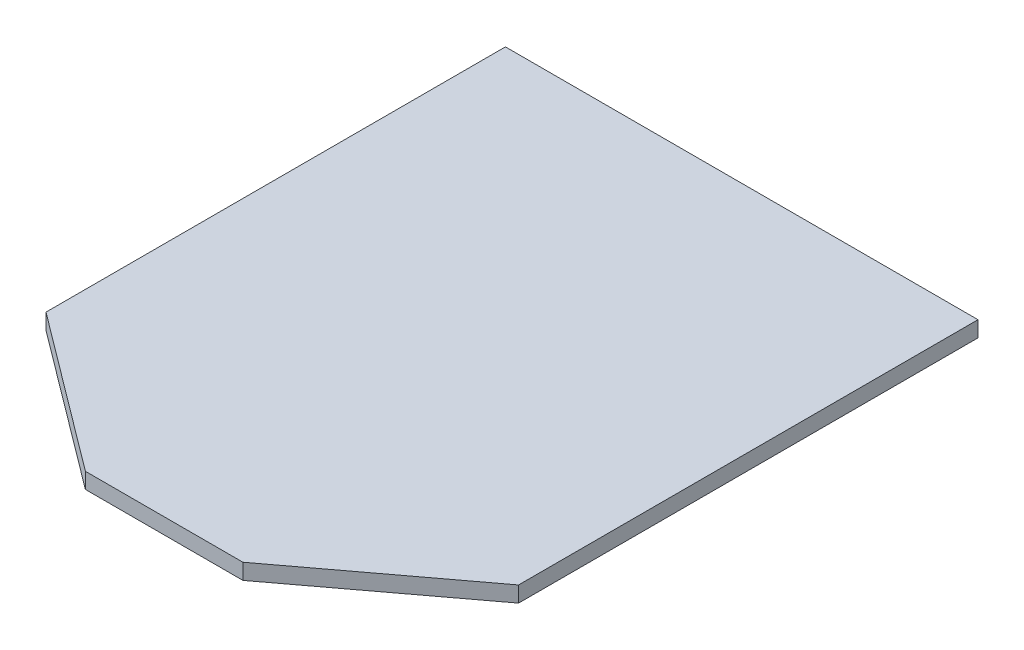
SolidWorks part; units mm, degrees
ref_plane "Front Plane" through (0, 0, 0) normal (0, 0, 1) x (1, 0, 0)
ref_plane "Top Plane" through (0, 0, 0) normal (0, 1, 0) x (1, 0, 0)
ref_plane "Right Plane" through (0, 0, 0) normal (1, 0, 0) x (0, 0, -1)
sketch "Sketch1" plane through (0, 0, 0) normal (0, 1, 0) x (1, 0, 0)
  line L1 (-90, -110) -> (90, -110)
  line L2 (-90, -110) -> (-90, 110)
  line L3 (-90, 110) -> (90, 110)
  line L4 (90, -110) -> (90, 110)
  line L5 (-90, -110) -> (90, 110) construction
  line L6 (-90, 110) -> (90, -110) construction
  point P0 (0, 0)
  dimension "D1" = 180
  dimension "D2" = 220
extrude "Boss-Extrude1" add sketch "Sketch1" along normal blind 6
sketch "Sketch2" plane through (0, 6, 0) normal (0, 1, 0) x (1, 0, 0)
  line L0 (-90, -110) -> (-30, -110)
  line L1 (-90, -110) -> (90, -110) construction
  line L2 (-30, -110) -> (-90, -65)
  line L3 (-90, 110) -> (-90, -110) construction
  line L4 (-90, -65) -> (-90, -110)
  line L5 (30, -110) -> (90, -65)
  line L6 (90, -110) -> (90, 110) construction
  line L7 (90, -65) -> (90, -110)
  line L8 (90, -110) -> (30, -110)
extrude "Cut-Extrude1" cut sketch "Sketch2" against normal through all
